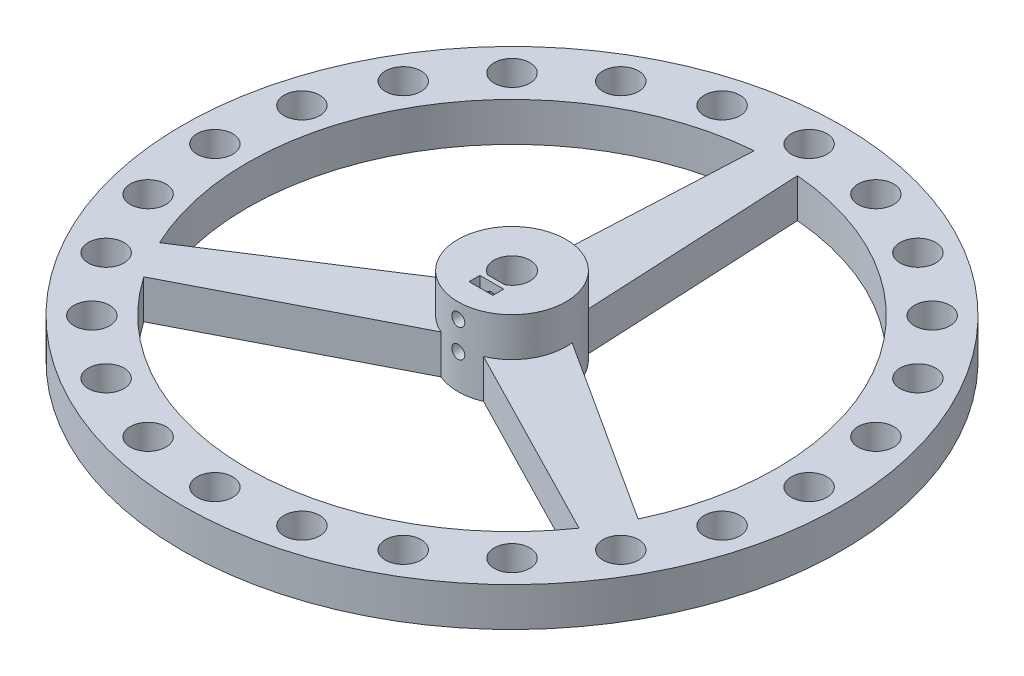
SolidWorks part; units mm, degrees
ref_plane "Front Plane" through (0, 0, 0) normal (0, 0, 1) x (1, 0, 0)
ref_plane "Top Plane" through (0, 0, 0) normal (0, 1, 0) x (1, 0, 0)
ref_plane "Right Plane" through (0, 0, 0) normal (1, 0, 0) x (0, 0, -1)
sketch "Sketch1" plane through (0, 0, 0) normal (0, 1, 0) x (1, 0, 0)
  line L0 (0, 61.2) -> (0, 0) construction
  line L1 (-7.5, 10) -> (-5, 60.9954)
  line L2 (5, 60.9954) -> (7.5, 10)
  line L3 (12.4103, 1.4952) -> (55.3236, -26.1676)
  line L4 (50.3236, -34.8278) -> (4.9103, -11.4952)
  line L5 (-4.9103, -11.4952) -> (-50.3236, -34.8278)
  line L6 (-55.3236, -26.1676) -> (-12.4103, 1.4952)
  circle A2 centre (0, 0) radius 76.2
  arc A3 (-50.3236, -34.8278) -> (50.3236, -34.8278) centre (0, 0) ccw
  arc A4 (12.4103, 1.4952) -> (7.5, 10) centre (0, 0) ccw
  arc A5 (55.3236, -26.1676) -> (5, 60.9954) centre (0, 0) ccw
  arc A6 (-4.9103, -11.4952) -> (4.9103, -11.4952) centre (0, 0) ccw
  arc A7 (-7.5, 10) -> (-12.4103, 1.4952) centre (0, 0) ccw
  arc A8 (-5, 60.9954) -> (-55.3236, -26.1676) centre (0, 0) ccw
  dimension "D1" = 152.4
  dimension "D2" = 15
  dimension "D3" = 25
  dimension "D4" = 10
  dimension "D5" = 15
  dimension "D6" = 3
extrude "Boss-Extrude1" add sketch "Sketch1" along normal blind 9
sketch "Sketch2" plane through (0, 9, 0) normal (0, 1, 0) x (1, 0, 0)
  circle A0 centre (0, 0) radius 12.5
  arc A1 (12.4103, 1.4952) -> (7.5, 10) centre (0, 0) ccw construction
extrude "Boss-Extrude2" add sketch "Sketch2" along normal blind 9
sketch "Sketch3" plane through (0, 18, 0) normal (0, -1, 0) x (1, 0, 0)
  line L0 (0, 0) -> (0, 4.175) construction
  line L1 (-1.9812, 3.675) -> (1.9812, 3.675)
  circle A0 centre (0, 0) radius 4.175 construction
  arc A1 (-1.9812, 3.675) -> (1.9812, 3.675) centre (0, 0) ccw
  point P8 (0, 3.675)
  dimension "D1" = 8.35
  dimension "D2" = 0.5
extrude "Cut-Extrude1" cut sketch "Sketch3" along normal blind 13
sketch "Sketch4" plane through (0, 0, 3.675) normal (0, 0, -1) x (-1, 0, 0)
  line L0 (0, 0) -> (0, 8) construction
  line L1 (0, 11.1754) -> (-2.75, 9.5877)
  line L2 (-2.75, 9.5877) -> (-2.75, 6.4123)
  line L3 (-2.75, 6.4123) -> (0, 4.8246)
  line L4 (0, 4.8246) -> (2.75, 6.4123)
  line L5 (2.75, 6.4123) -> (2.75, 9.5877)
  line L6 (2.75, 9.5877) -> (0, 11.1754)
  circle A0 centre (0, 8) radius 2.75 construction
  dimension "D1" = 8
  dimension "D2" = 5.5
extrude "Cut-Extrude2" cut sketch "Sketch4" against normal blind 2.5 from offset 1 offset against normal yes
sketch "Sketch5" plane through (0, 0, 7.175) normal (0, 0, -1) x (-1, 0, 0)
  line L0 (0, 11.1754) -> (0, 4.8246) construction
  line L1 (0, 11.1754) -> (0, 14.5) construction
  circle A0 centre (0, 8) radius 1.5
  circle A1 centre (0, 14.5) radius 1.5
  dimension "D1" = 3
  dimension "D2" = 6.5
extrude "Cut-Extrude3" cut sketch "Sketch5" against normal up to next and the other way up to next
ref_plane "Plane4" through (0, 9.5877, 0) normal (0, 1, 0) x (1, 0, 0)
sketch "Sketch6" plane through (0, 9.5877, 0) normal (0, 1, 0) x (1, 0, 0)
  line L0 (2.75, -7.175) -> (2.75, -4.675) construction
  line L1 (2.75, -7.175) -> (-2.75, -7.175)
  line L2 (2.75, -7.175) -> (2.75, -4.675)
  line L3 (2.75, -4.675) -> (-2.75, -4.675)
  line L4 (-2.75, -7.175) -> (-2.75, -4.675)
  line L5 (2.75, -7.175) -> (-2.75, -4.675) construction
  line L6 (2.75, -4.675) -> (-2.75, -7.175) construction
  line L7 (-2.75, -7.175) -> (-2.75, -4.675) construction
  line L9 (-2.75, -7.175) -> (0, -7.175) construction
  line L10 (-1.5, -4.675) -> (1.5, -4.675) construction
  point P4 (0, -5.925)
extrude "Cut-Extrude4" cut sketch "Sketch6" along normal through all
sketch "Sketch7" plane through (0, 9, 0) normal (0, 1, 0) x (1, 0, 0)
  line L0 (0, 0.6676) -> (0, 61.2) construction
  line L1 (0, 61.2) -> (0, 68.7) construction
  line L2 (0, 68.7) -> (0, 76.2) construction
  circle A0 centre (0, 0) radius 68.7 construction
  arc A1 (-5, 60.9954) -> (-55.3236, -26.1676) centre (0, 0) ccw construction
  circle A2 centre (0, 0) radius 76.2 construction
  circle A3 centre (0, 68.7) radius 4.125
  dimension "D1" = 8.25
extrude "Cut-Extrude5" cut sketch "Sketch7" against normal through all
pattern_circular "CirPattern1" count 24 over 360 about axis through (0, 0, 0) along (0, 1, 0) of "Cut-Extrude5"
